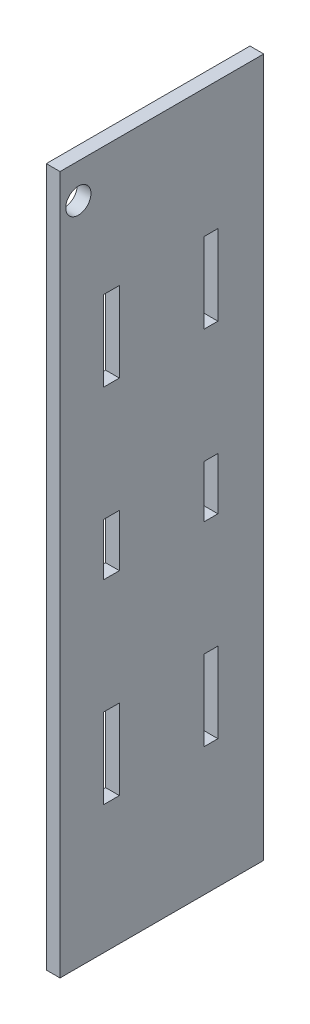
SolidWorks part; units mm, degrees
ref_plane "Front Plane" through (0, 0, 0) normal (1, 0, 0) x (0, 1, 0)
ref_plane "Top Plane" through (0, 0, 0) normal (0, 0, 1) x (0, 1, 0)
ref_plane "Right Plane" through (0, 0, 0) normal (0, 1, 0) x (-1, 0, 0)
sketch "Sketch1" plane through (0, 0, 0) normal (1, 0, 0) x (0, 1, 0)
  line L0 (-82.0131, -12.297) -> (-49.7598, -12.297) construction
  line L1 (-49.7598, 56.603) -> (255.0402, 56.603)
  line L2 (-49.7598, 56.603) -> (-49.7598, -32.297)
  line L3 (-49.7598, -32.297) -> (255.0402, -32.297)
  line L4 (255.0402, 56.603) -> (255.0402, -32.297)
  line L5 (91.2402, -12.297) -> (114.0402, -12.297) construction
  line L6 (6.2402, -12.297) -> (6.2402, -6.297)
  line L7 (6.2402, -6.297) -> (41.2402, -6.297)
  line L8 (41.2402, -6.297) -> (41.2402, -12.297)
  line L9 (164.0402, -12.297) -> (199.0402, -12.297) construction
  line L10 (91.2402, -12.297) -> (91.2402, -6.297)
  line L11 (91.2402, -6.297) -> (114.0402, -6.297)
  line L12 (114.0402, -6.297) -> (114.0402, -12.297)
  line L13 (255.0402, -12.297) -> (295.7345, -12.297) construction
  line L14 (164.0402, -12.297) -> (164.0402, -6.297)
  line L15 (164.0402, -6.297) -> (199.0402, -6.297)
  line L16 (199.0402, -6.297) -> (199.0402, -12.297)
  line L17 (6.2402, 30.703) -> (41.2402, 30.703)
  line L18 (6.2402, -12.297) -> (41.2402, -12.297)
  line L19 (91.2402, -12.297) -> (114.0402, -12.297)
  line L20 (164.0402, -12.297) -> (199.0402, -12.297)
  line L21 (6.2402, -12.297) -> (41.2402, -12.297) construction
  line L22 (91.2402, 30.703) -> (114.0402, 30.703)
  line L23 (164.0402, 30.703) -> (199.0402, 30.703)
  line L24 (6.2402, 30.703) -> (6.2402, 37.703)
  line L25 (6.2402, 37.703) -> (41.2402, 37.703)
  line L26 (41.2402, 37.703) -> (41.2402, 30.703)
  line L27 (91.2402, 30.703) -> (91.2402, 37.703)
  line L28 (91.2402, 37.703) -> (114.0402, 37.703)
  line L29 (114.0402, 37.703) -> (114.0402, 30.703)
  line L30 (164.0402, 30.703) -> (164.0402, 37.703)
  line L31 (164.0402, 37.703) -> (199.0402, 37.703)
  line L32 (199.0402, 37.703) -> (199.0402, 30.703)
  line L33 (249.0402, 62.8702) -> (249.0402, -46.1038) construction
  line L34 (234.0402, 60.7961) -> (234.0402, -49.614) construction
  circle A0 centre (240.0402, 48.603) radius 5.5
  circle A1 centre (240.0402, 48.603) radius 3 construction
  dimension "D17" = 11
  dimension "D20" = 6
  dimension "D1" = 88.9
  dimension "D2" = 304.8
  dimension "D3" = 20
  dimension "D4" = 56
  dimension "D5" = 50
  dimension "D6" = 50
  dimension "D7" = 56
  dimension "D8" = 35
  dimension "D9" = 35
  dimension "D11" = 6
  dimension "D12" = 6
  dimension "D13" = 6
  dimension "D14" = 7
  dimension "D15" = 15
  dimension "D16" = 8
  dimension "D18" = 6
  dimension "D19" = 15
  dimension "D10" = 37
extrude "Boss-Extrude1" add sketch "Sketch1" along normal blind 6
